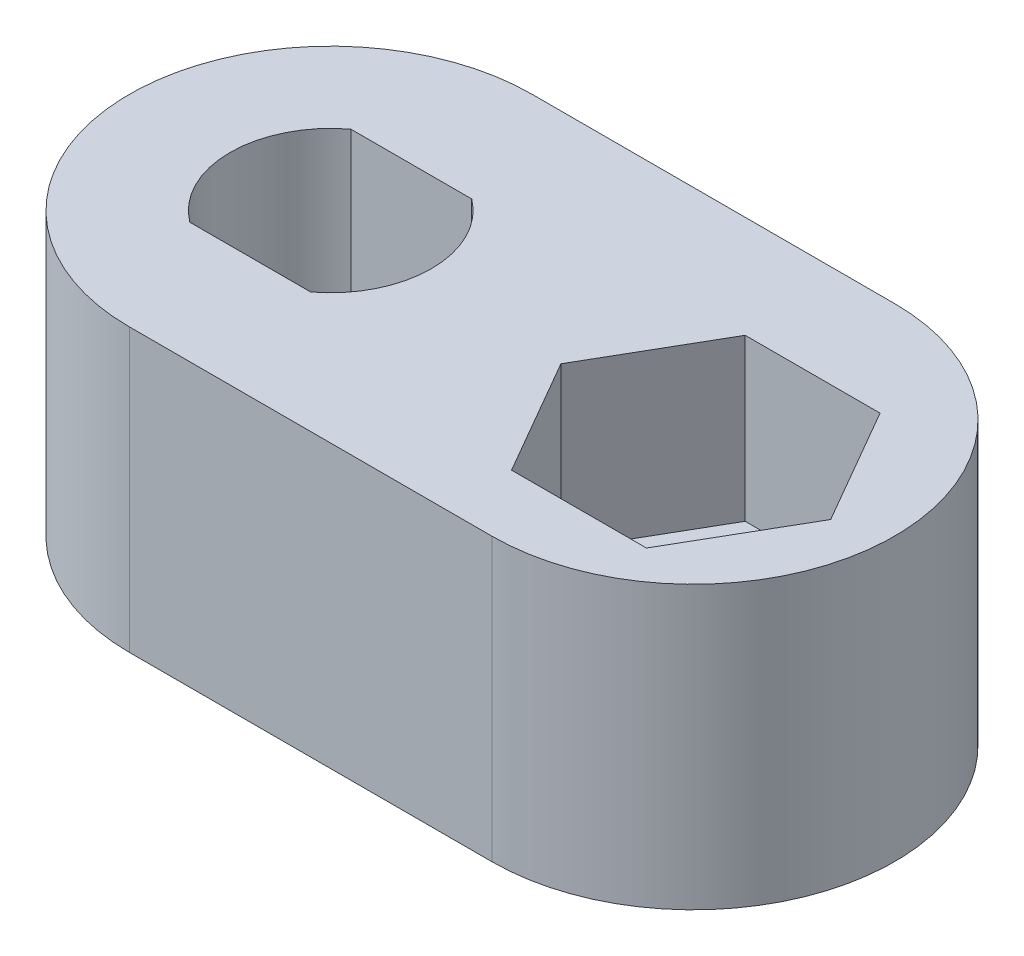
SolidWorks part; units mm, degrees
ref_plane "前视基准面" through (0, 0, 0) normal (0, 0, 1) x (1, 0, 0)
ref_plane "上视基准面" through (0, 0, 0) normal (0, 1, 0) x (1, 0, 0)
ref_plane "右视基准面" through (0, 0, 0) normal (1, 0, 0) x (0, 0, -1)
sketch "草图1" plane through (0, 0, 0) normal (0, 1, 0) x (1, 0, 0)
  line L0 (-4.5, 0) -> (4.5, 0) construction
  line L1 (-4.5, 5) -> (4.5, 5)
  line L2 (-4.5, -5) -> (4.5, -5)
  arc A0 (-4.5, 5) -> (-4.5, -5) centre (-4.5, 0) ccw
  arc A1 (4.5, -5) -> (4.5, 5) centre (4.5, 0) ccw
  point P2 (0, 0)
  dimension "D1" = 10
  dimension "D2" = 9
extrude "凸台-拉伸1" add sketch "草图1" along normal blind 7
sketch "草图2" plane through (0, 7, 0) normal (0, 1, 0) x (1, 0, 0)
  line L0 (0, 0) -> (-9.1692, 0) construction
  line L1 (-6, 2) -> (-3, 2)
  line L2 (-6, -2) -> (-3, -2)
  circle A0 centre (-4.5, 0) radius 2.5
  point P8 (-4.5, 0)
  dimension "D2" = 5
  dimension "D1" = 4
extrude "切除-拉伸1" cut sketch "草图2" against normal blind 4
hole_wizard "M3 六角凹锥坑螺钉的锥形沉头孔1" positions "草图8" profile "草图9" countersink size "M3" standard "ISO"
sketch "草图8" plane through (0, 0, 0) normal (0, -1, 0) x (-1, 0, 0)
  point P0 (4.5, 0)
sketch "草图9" plane through (-4.5, 0, 0) normal (1, 0, 0) x (0, 0, -1)
  line L0 (0, 0) -> (0, 8.5215)
  line L1 (0, 8.5215) -> (1.7, 7.5)
  line L2 (1.7, 7.5) -> (1.7, 1.66)
  line L3 (1.7, 1.66) -> (3.36, 0)
  line L5 (3.36, 0) -> (0, 0)
  line L6 (-1.7, 1.66) -> (-3.36, 0) construction
  line L10 (0, 8.5215) -> (-1.7, 7.5) construction
  line L11 (0, -6.35) -> (0, 107.95) construction
  dimension "孔直径" = 3.4
  dimension "孔深度" = 7.5
  dimension "近端锥形沉头孔直径" = 6.72
  dimension "近端锥形沉头孔角度" = 90
  dimension "导头角度" = 118
hole_wizard "孔1" positions "草图10" profile "草图11" legacy end condition through all
sketch "草图10" plane through (0, 7, 0) normal (0, 1, 0) x (1, 0, 0)
  point P0 (5, -0.4368)
sketch "草图11" plane through (5, 7, 0.4368) normal (1, 0, 0) x (0, 0, 1)
  line L0 (0, 0) -> (0, 7)
  line L1 (0, 7) -> (2.075, 7)
  line L2 (2.075, 7) -> (2.075, 0)
  line L3 (2.075, 0) -> (0, 0)
  line L4 (0, 110) -> (0, -10) construction
  dimension "直径" = 4.15
  dimension "深度" = 7
sketch "草图12" plane through (0, 7, 0) normal (0, 1, 0) x (1, 0, 0)
  line L0 (4.5, 5) -> (-4.5, 5) construction
  line L1 (8.3486, -0.4368) -> (6.6743, 2.4632)
  line L2 (6.6743, 2.4632) -> (3.3257, 2.4632)
  line L3 (3.3257, 2.4632) -> (1.6514, -0.4368)
  line L4 (1.6514, -0.4368) -> (3.3257, -3.3368)
  line L5 (3.3257, -3.3368) -> (6.6743, -3.3368)
  line L6 (6.6743, -3.3368) -> (8.3486, -0.4368)
  circle A0 centre (5, -0.4368) radius 2.9 construction
  dimension "D1" = 5.8
extrude "切除-拉伸2" cut sketch "草图12" against normal blind 4
